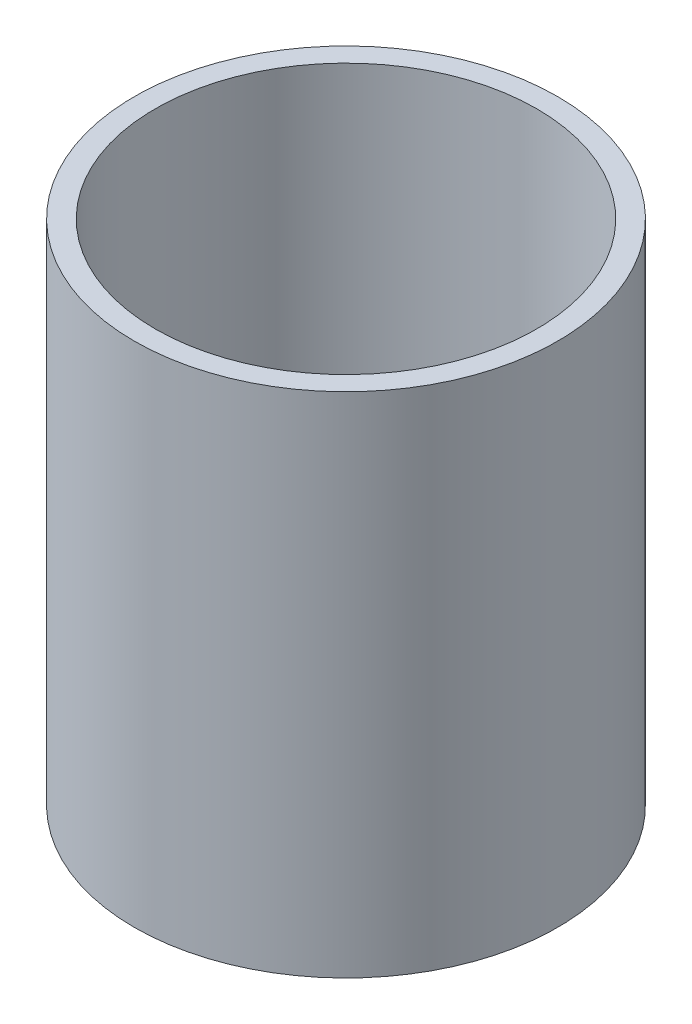
SolidWorks part; units mm, degrees
ref_plane "Front Plane" through (0, 0, 0) normal (0, 0, 1) x (1, 0, 0)
ref_plane "Top Plane" through (0, 0, 0) normal (0, 1, 0) x (1, 0, 0)
ref_plane "Right Plane" through (0, 0, 0) normal (1, 0, 0) x (0, 0, -1)
sketch "Sketch2" plane through (0, 0, 0) normal (0, 1, 0) x (1, 0, 0)
  circle A0 centre (0, 0) radius 63.5573
extrude "Boss-Extrude1" add sketch "Sketch2" along normal blind 152.4
sketch "Sketch4" plane through (0, 0, 0) normal (0, -1, 0) x (-1, 0, 0)
  circle A0 centre (0, 0) radius 57.2545
extrude "Cut-Extrude1" cut sketch "Sketch4" against normal blind 152.4
